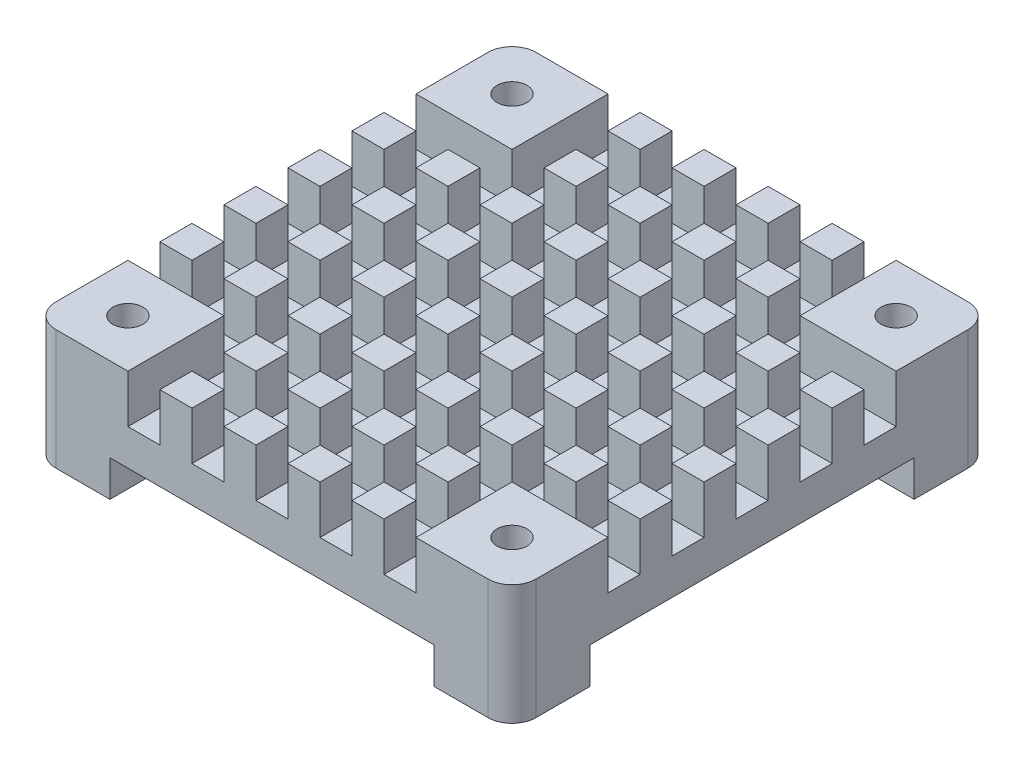
SolidWorks part; units mm, degrees
ref_plane "前视基准面" through (0, 0, 0) normal (0, 0, 1) x (1, 0, 0)
ref_plane "上视基准面" through (0, 0, 0) normal (0, 1, 0) x (1, 0, 0)
ref_plane "右视基准面" through (0, 0, 0) normal (1, 0, 0) x (0, 0, -1)
other "Configuration Table"
sketch "草图2" plane through (0, 0, 0) normal (0, 1, 0) x (1, 0, 0)
  line L1 (-20, -20) -> (20, -20)
  line L2 (-20, -20) -> (-20, 20)
  line L3 (-20, 20) -> (20, 20)
  line L4 (20, -20) -> (20, 20)
  line L5 (-20, -20) -> (20, 20) construction
  line L6 (-20, 20) -> (20, -20) construction
  line L7 (-16, -16) -> (16, -16) construction
  line L8 (-16, -16) -> (-16, 16) construction
  line L9 (-16, 16) -> (16, 16) construction
  line L10 (16, -16) -> (16, 16) construction
  line L11 (-16, -16) -> (16, 16) construction
  line L12 (-16, 16) -> (16, -16) construction
  circle A0 centre (-16, 16) radius 1.25
  circle A1 centre (16, 16) radius 1.25
  circle A2 centre (16, -16) radius 1.25
  circle A3 centre (-16, -16) radius 1.25
  point P0 (0, 0)
  point P5 (0, 0)
  point P21 (0, 0)
  dimension "D3" = 2.5
  dimension "D1" = 40
  dimension "D2" = 32
  dimension "D4" = 4
extrude "凸台-拉伸1" add sketch "草图2" along normal blind 3
sketch "草图3" plane through (0, 3, 0) normal (0, 1, 0) x (1, 0, 0)
  line L1 (9.3333, -14.6667) -> (6.6667, -14.6667)
  line L4 (20, -20) -> (20, 20)
  line L5 (20, 20) -> (-20, 20)
  line L6 (-20, 20) -> (-20, -20)
  line L7 (-20, -20) -> (20, -20)
  line L8 (20, -20) -> (20, -12)
  line L9 (20, 20) -> (12, 20)
  line L10 (-20, 20) -> (-20, 12)
  line L11 (-20, -20) -> (-12, -20)
  line L12 (20, 9.3333) -> (17.3333, 9.3333)
  line L13 (20, 6.6667) -> (17.3333, 6.6667)
  line L14 (20, 4) -> (17.3333, 4)
  line L15 (20, 1.3333) -> (17.3333, 1.3333)
  line L17 (20, -1.3333) -> (17.3333, -1.3333)
  line L18 (-20, 12) -> (-12, 12)
  line L19 (20, -4) -> (17.3333, -4)
  line L20 (20, -6.6667) -> (17.3333, -6.6667)
  line L21 (20, -9.3333) -> (17.3333, -9.3333)
  line L23 (-12, 9.3333) -> (-14.6667, 9.3333)
  line L25 (-12, 6.6667) -> (-14.6667, 6.6667)
  line L29 (-12, 20) -> (-12, 12)
  line L30 (-9.3333, 20) -> (-9.3333, 17.3333)
  line L31 (-6.6667, 20) -> (-6.6667, 17.3333)
  line L32 (-20, 4) -> (-20, 1.3333)
  line L33 (-4, 20) -> (-4, 17.3333)
  line L34 (-1.3333, 20) -> (-1.3333, 17.3333)
  line L35 (1.3333, 20) -> (1.3333, 17.3333)
  line L36 (4, 20) -> (4, 17.3333)
  line L37 (6.6667, 20) -> (6.6667, 17.3333)
  line L38 (9.3333, 20) -> (9.3333, 17.3333)
  line L39 (12, 20) -> (12, 12)
  line L40 (-12, 4) -> (-14.6667, 4)
  line L46 (9.3333, -17.3333) -> (6.6667, -17.3333)
  line L47 (-17.3333, 9.3333) -> (-17.3333, 6.6667)
  line L48 (-14.6667, 9.3333) -> (-14.6667, 6.6667)
  line L51 (9.3333, 17.3333) -> (6.6667, 17.3333)
  line L52 (9.3333, 14.6667) -> (6.6667, 14.6667)
  line L53 (12, 12) -> (20, 12)
  line L54 (14.6667, 9.3333) -> (14.6667, 6.6667)
  line L55 (17.3333, 9.3333) -> (17.3333, 6.6667)
  line L56 (-12, 1.3333) -> (-14.6667, 1.3333)
  line L57 (12, -12) -> (20, -12)
  line L59 (-17.3333, 17.3333) -> (-17.3333, 14.6667) [skipped]
  line L60 (-14.6667, 17.3333) -> (-14.6667, 14.6667) [skipped]
  line L61 (17.3333, 17.3333) -> (17.3333, 14.6667) [skipped]
  line L62 (14.6667, 17.3333) -> (14.6667, 14.6667) [skipped]
  line L63 (17.3333, 17.3333) -> (14.6667, 17.3333) [skipped]
  line L64 (17.3333, 14.6667) -> (14.6667, 14.6667) [skipped]
  line L65 (20, -14.6667) -> (17.3333, -14.6667) [skipped]
  line L66 (17.3333, -17.3333) -> (14.6667, -17.3333) [skipped]
  line L67 (-12, -1.3333) -> (-14.6667, -1.3333)
  line L68 (-12, -4) -> (-14.6667, -4)
  line L69 (-12, -6.6667) -> (-14.6667, -6.6667)
  line L70 (-12, -9.3333) -> (-14.6667, -9.3333)
  line L71 (-12, -12) -> (-20, -12)
  line L72 (-9.3333, -20) -> (-6.6667, -20)
  line L73 (-20, -12) -> (-20, -20)
  line L74 (-12, -12) -> (-12, -20)
  line L75 (-9.3333, -12) -> (-9.3333, -14.6667)
  line L76 (-6.6667, -12) -> (-6.6667, -14.6667)
  line L77 (-4, -12) -> (-4, -14.6667)
  line L78 (-1.3333, -12) -> (-1.3333, -14.6667)
  line L79 (1.3333, -12) -> (1.3333, -14.6667)
  line L80 (4, -12) -> (4, -14.6667)
  line L81 (6.6667, -12) -> (6.6667, -14.6667)
  line L82 (9.3333, -12) -> (9.3333, -14.6667)
  line L83 (12, -12) -> (12, -20)
  line L84 (20, -9.3333) -> (20, -6.6667)
  line L85 (9.3333, 12) -> (6.6667, 12)
  line L86 (9.3333, 9.3333) -> (6.6667, 9.3333)
  line L87 (9.3333, 6.6667) -> (6.6667, 6.6667)
  line L88 (9.3333, 4) -> (6.6667, 4)
  line L89 (9.3333, 1.3333) -> (6.6667, 1.3333)
  line L90 (9.3333, -1.3333) -> (6.6667, -1.3333)
  line L91 (9.3333, -4) -> (6.6667, -4)
  line L92 (9.3333, -6.6667) -> (6.6667, -6.6667)
  line L93 (9.3333, -9.3333) -> (6.6667, -9.3333)
  line L94 (9.3333, -12) -> (6.6667, -12)
  line L95 (12, -20) -> (20, -20)
  line L96 (-20, 9.3333) -> (-20, 6.6667)
  line L97 (-12, 9.3333) -> (-12, 6.6667)
  line L98 (-9.3333, 9.3333) -> (-9.3333, 6.6667)
  line L99 (-6.6667, 9.3333) -> (-6.6667, 6.6667)
  line L100 (-4, 9.3333) -> (-4, 6.6667)
  line L101 (-1.3333, 9.3333) -> (-1.3333, 6.6667)
  line L102 (1.3333, 9.3333) -> (1.3333, 6.6667)
  line L103 (4, 9.3333) -> (4, 6.6667)
  line L104 (6.6667, 9.3333) -> (6.6667, 6.6667)
  line L105 (9.3333, 9.3333) -> (9.3333, 6.6667)
  line L106 (12, 9.3333) -> (12, 6.6667)
  line L107 (20, 12) -> (20, 20)
  line L108 (-12, 20) -> (-20, 20)
  line L109 (9.3333, 20) -> (6.6667, 20)
  line L110 (20, 12) -> (12, 12) [skipped]
  line L111 (20, -12) -> (12, -12) [skipped]
  line L112 (-17.3333, 4) -> (-17.3333, 1.3333)
  line L113 (-14.6667, 4) -> (-14.6667, 1.3333)
  line L114 (-12, 4) -> (-12, 1.3333)
  line L115 (-9.3333, 4) -> (-9.3333, 1.3333)
  line L116 (-6.6667, 4) -> (-6.6667, 1.3333)
  line L117 (-4, 4) -> (-4, 1.3333)
  line L118 (-1.3333, 4) -> (-1.3333, 1.3333)
  line L119 (1.3333, 4) -> (1.3333, 1.3333)
  line L120 (4, 4) -> (4, 1.3333)
  line L121 (6.6667, 4) -> (6.6667, 1.3333)
  line L122 (9.3333, 4) -> (9.3333, 1.3333)
  line L123 (12, 4) -> (12, 1.3333)
  line L124 (14.6667, 4) -> (14.6667, 1.3333)
  line L125 (17.3333, 4) -> (17.3333, 1.3333)
  line L126 (20, 6.6667) -> (20, 9.3333)
  line L127 (-20, -1.3333) -> (-20, -4)
  line L128 (-17.3333, -1.3333) -> (-17.3333, -4)
  line L129 (-14.6667, -1.3333) -> (-14.6667, -4)
  line L130 (-12, -1.3333) -> (-12, -4)
  line L131 (-9.3333, -1.3333) -> (-9.3333, -4)
  line L132 (-6.6667, -1.3333) -> (-6.6667, -4)
  line L133 (-4, -1.3333) -> (-4, -4)
  line L134 (-1.3333, -1.3333) -> (-1.3333, -4)
  line L135 (1.3333, -1.3333) -> (1.3333, -4)
  line L136 (4, -1.3333) -> (4, -4)
  line L137 (6.6667, -1.3333) -> (6.6667, -4)
  line L138 (9.3333, -1.3333) -> (9.3333, -4)
  line L139 (12, -1.3333) -> (12, -4)
  line L140 (14.6667, -1.3333) -> (14.6667, -4)
  line L141 (17.3333, -1.3333) -> (17.3333, -4)
  line L142 (20, 1.3333) -> (20, 4)
  line L143 (-20, -6.6667) -> (-20, -9.3333)
  line L144 (-17.3333, -6.6667) -> (-17.3333, -9.3333)
  line L145 (-14.6667, -6.6667) -> (-14.6667, -9.3333)
  line L146 (-12, -6.6667) -> (-12, -9.3333)
  line L147 (-9.3333, -6.6667) -> (-9.3333, -9.3333)
  line L148 (-6.6667, -6.6667) -> (-6.6667, -9.3333)
  line L149 (-4, -6.6667) -> (-4, -9.3333)
  line L150 (-1.3333, -6.6667) -> (-1.3333, -9.3333)
  line L151 (1.3333, -6.6667) -> (1.3333, -9.3333)
  line L152 (4, -6.6667) -> (4, -9.3333)
  line L153 (6.6667, -6.6667) -> (6.6667, -9.3333)
  line L154 (9.3333, -6.6667) -> (9.3333, -9.3333)
  line L155 (12, -6.6667) -> (12, -9.3333)
  line L156 (14.6667, -6.6667) -> (14.6667, -9.3333)
  line L157 (17.3333, -6.6667) -> (17.3333, -9.3333)
  line L158 (20, -4) -> (20, -1.3333)
  line L159 (-6.6667, 20) -> (-9.3333, 20)
  line L160 (-6.6667, 17.3333) -> (-9.3333, 17.3333)
  line L161 (-6.6667, 14.6667) -> (-9.3333, 14.6667)
  line L162 (-6.6667, 12) -> (-9.3333, 12)
  line L163 (-6.6667, 9.3333) -> (-9.3333, 9.3333)
  line L164 (-6.6667, 6.6667) -> (-9.3333, 6.6667)
  line L165 (-6.6667, 4) -> (-9.3333, 4)
  line L166 (-6.6667, 1.3333) -> (-9.3333, 1.3333)
  line L167 (-6.6667, -1.3333) -> (-9.3333, -1.3333)
  line L168 (-6.6667, -4) -> (-9.3333, -4)
  line L169 (-6.6667, -6.6667) -> (-9.3333, -6.6667)
  line L170 (-6.6667, -9.3333) -> (-9.3333, -9.3333)
  line L171 (-6.6667, -12) -> (-9.3333, -12)
  line L172 (-6.6667, -14.6667) -> (-9.3333, -14.6667)
  line L173 (-6.6667, -17.3333) -> (-9.3333, -17.3333)
  line L174 (-4, -20) -> (-1.3333, -20)
  line L175 (-1.3333, 20) -> (-4, 20)
  line L176 (-1.3333, 17.3333) -> (-4, 17.3333)
  line L177 (-1.3333, 14.6667) -> (-4, 14.6667)
  line L178 (-1.3333, 12) -> (-4, 12)
  line L179 (-1.3333, 9.3333) -> (-4, 9.3333)
  line L180 (-1.3333, 6.6667) -> (-4, 6.6667)
  line L181 (-1.3333, 4) -> (-4, 4)
  line L182 (-1.3333, 1.3333) -> (-4, 1.3333)
  line L183 (-1.3333, -1.3333) -> (-4, -1.3333)
  line L184 (-1.3333, -4) -> (-4, -4)
  line L185 (-1.3333, -6.6667) -> (-4, -6.6667)
  line L186 (-1.3333, -9.3333) -> (-4, -9.3333)
  line L187 (-1.3333, -12) -> (-4, -12)
  line L188 (-1.3333, -14.6667) -> (-4, -14.6667)
  line L189 (-1.3333, -17.3333) -> (-4, -17.3333)
  line L190 (1.3333, -20) -> (4, -20)
  line L191 (4, 20) -> (1.3333, 20)
  line L192 (4, 17.3333) -> (1.3333, 17.3333)
  line L193 (4, 14.6667) -> (1.3333, 14.6667)
  line L194 (4, 12) -> (1.3333, 12)
  line L195 (4, 9.3333) -> (1.3333, 9.3333)
  line L196 (4, 6.6667) -> (1.3333, 6.6667)
  line L197 (4, 4) -> (1.3333, 4)
  line L198 (4, 1.3333) -> (1.3333, 1.3333)
  line L199 (4, -1.3333) -> (1.3333, -1.3333)
  line L200 (4, -4) -> (1.3333, -4)
  line L201 (4, -6.6667) -> (1.3333, -6.6667)
  line L202 (4, -9.3333) -> (1.3333, -9.3333)
  line L203 (4, -12) -> (1.3333, -12)
  line L204 (4, -14.6667) -> (1.3333, -14.6667)
  line L205 (4, -17.3333) -> (1.3333, -17.3333)
  line L206 (6.6667, -20) -> (9.3333, -20)
  line L207 (-17.3333, 9.3333) -> (-20, 9.3333)
  line L208 (-17.3333, 6.6667) -> (-20, 6.6667)
  line L209 (-17.3333, 4) -> (-20, 4)
  line L210 (-17.3333, 1.3333) -> (-20, 1.3333)
  line L211 (-17.3333, -1.3333) -> (-20, -1.3333)
  line L212 (-17.3333, -4) -> (-20, -4)
  line L213 (-17.3333, -6.6667) -> (-20, -6.6667)
  line L214 (-17.3333, -9.3333) -> (-20, -9.3333)
  line L215 (14.6667, 9.3333) -> (12, 9.3333)
  line L216 (14.6667, 6.6667) -> (12, 6.6667)
  line L217 (14.6667, 4) -> (12, 4)
  line L218 (14.6667, 1.3333) -> (12, 1.3333)
  line L219 (14.6667, -1.3333) -> (12, -1.3333)
  line L220 (14.6667, -4) -> (12, -4)
  line L221 (14.6667, -6.6667) -> (12, -6.6667)
  line L222 (14.6667, -9.3333) -> (12, -9.3333)
  line L223 (-9.3333, -17.3333) -> (-9.3333, -20)
  line L224 (-6.6667, -17.3333) -> (-6.6667, -20)
  line L225 (-4, -17.3333) -> (-4, -20)
  line L226 (-1.3333, -17.3333) -> (-1.3333, -20)
  line L227 (1.3333, -17.3333) -> (1.3333, -20)
  line L228 (4, -17.3333) -> (4, -20)
  line L229 (6.6667, -17.3333) -> (6.6667, -20)
  line L230 (9.3333, -17.3333) -> (9.3333, -20)
  line L231 (-9.3333, 14.6667) -> (-9.3333, 12)
  line L232 (-6.6667, 14.6667) -> (-6.6667, 12)
  line L233 (-4, 14.6667) -> (-4, 12)
  line L234 (-1.3333, 14.6667) -> (-1.3333, 12)
  line L235 (1.3333, 14.6667) -> (1.3333, 12)
  line L236 (4, 14.6667) -> (4, 12)
  line L237 (6.6667, 14.6667) -> (6.6667, 12)
  line L238 (9.3333, 14.6667) -> (9.3333, 12)
  circle A0 centre (16, 16) radius 1.25 construction
  circle A1 centre (16, -16) radius 1.25 construction
  circle A2 centre (-16, -16) radius 1.25 construction
  circle A3 centre (-16, 16) radius 1.25 construction
  circle A4 centre (16, 16) radius 1.25
  circle A5 centre (16, -16) radius 1.25
  circle A6 centre (-16, -16) radius 1.25
  circle A7 centre (-16, 16) radius 1.25
  dimension "D2" = 15
  dimension "D3" = 15
  dimension "D1" = 0
extrude "凸台-拉伸2" add sketch "草图3" along normal blind 4
sketch "草图4" plane through (0, 0, 0) normal (0, -1, 0) x (1, 0, 0)
  line L0 (-20, 13.5) -> (-13.5, 13.5)
  line L1 (-20, -13.5) -> (-13.5, -13.5)
  line L2 (-13.5, 20) -> (-13.5, 13.5)
  line L3 (13.5, 20) -> (13.5, 13.5)
  line L4 (20, -20) -> (20, 20)
  line L5 (20, 20) -> (-20, 20)
  line L6 (-20, 20) -> (-20, -20)
  line L7 (-20, -20) -> (20, -20)
  line L8 (20, -20) -> (20, -13.5)
  line L9 (20, 20) -> (13.5, 20)
  line L10 (-20, 20) -> (-20, -20)
  line L11 (-20, -20) -> (-13.5, -20)
  line L12 (-13.5, -13.5) -> (-13.5, -20)
  line L13 (13.5, -13.5) -> (13.5, -20)
  line L14 (20, 13.5) -> (20, 20)
  line L15 (-13.5, 20) -> (-20, 20)
  line L16 (13.5, 13.5) -> (20, 13.5)
  line L17 (13.5, -13.5) -> (20, -13.5)
  line L18 (13.5, -20) -> (20, -20)
  circle A0 centre (-16, -16) radius 1.25 construction
  circle A1 centre (16, -16) radius 1.25 construction
  circle A2 centre (16, 16) radius 1.25 construction
  circle A3 centre (-16, 16) radius 1.25 construction
  circle A4 centre (-16, -16) radius 1.25
  circle A5 centre (16, -16) radius 1.25
  circle A6 centre (16, 16) radius 1.25
  circle A7 centre (-16, 16) radius 1.25
  circle M9 centre (16, 16) radius 1.25
  circle M10 centre (-16, -16) radius 1.25
  line M11 (20, -20) -> (20, 20)
  line M12 (20, 20) -> (-20, 20)
  line M13 (-20, 20) -> (-20, -20)
  line M14 (-20, -20) -> (20, -20)
  circle M15 centre (16, -16) radius 1.25
  circle M16 centre (-16, 16) radius 1.25
  dimension "D2" = 6.5
  dimension "D3" = 6.5
  dimension "D4" = 6.5
  dimension "D5" = 6.5
  dimension "D1" = 0
extrude "凸台-拉伸3" add sketch "草图4" along normal blind 3 contours L2 L0 M12 M13 M16 | L3 L16 M11 M12 M9 | L17 L13 M14 M11 M15 | L12 L1 M13 M14 M10 | A4
fillet "圆角1" radius 2 4 edges at (20, 2, 20) (-20, 2, 20) (-20, 2, -20) (20, 2, -20)
